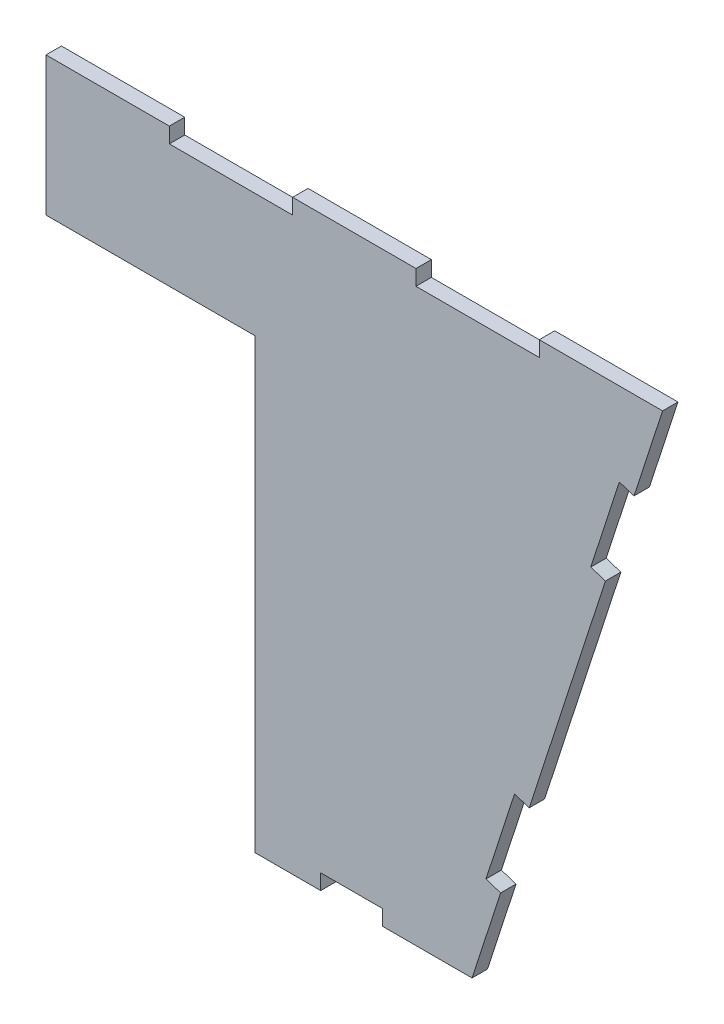
SolidWorks part; units mm, degrees
ref_plane "Front Plane" through (0, 0, 0) normal (0, 0, 1) x (1, 0, 0)
ref_plane "Top Plane" through (0, 0, 0) normal (0, 1, 0) x (1, 0, 0)
ref_plane "Right Plane" through (0, 0, 0) normal (1, 0, 0) x (0, 0, -1)
sketch "Sketch1" plane through (0, 0, 0) normal (0, 0, 1) x (1, 0, 0)
  line L0 (0, 0) -> (5.8868, 18.1176)
  line L1 (39.2452, 120.7842) -> (13.8452, 120.7842)
  line L2 (-87.7548, 120.7842) -> (-87.7548, 92.2092)
  line L4 (33.3584, 102.6666) -> (30.3388, 103.6477)
  line L5 (30.3388, 103.6477) -> (24.452, 85.5301)
  line L6 (24.452, 85.5301) -> (27.4716, 84.5489)
  line L7 (19.6226, 60.3921) -> (-40.3388, 79.8747) construction
  line L8 (33.3584, 102.6666) -> (39.2452, 120.7842)
  line L9 (8.7539, 37.2164) -> (11.7735, 36.2353)
  line L10 (2.8672, 19.0988) -> (8.7539, 37.2164)
  line L11 (5.8868, 18.1176) -> (2.8672, 19.0988)
  line L12 (11.7735, 36.2353) -> (27.4716, 84.5489)
  line L13 (-24.2548, 120.7842) -> (-24.2548, 85.5301) construction
  line L15 (-44.6599, 0) -> (-44.6599, 21.7121) construction
  line L16 (-62.3548, 120.7842) -> (-62.3548, 117.6092)
  line L17 (-62.3548, 117.6092) -> (-36.9548, 117.6092)
  line L18 (-36.9548, 117.6092) -> (-36.9548, 120.7842)
  line L19 (-62.3548, 120.7842) -> (-87.7548, 120.7842)
  line L20 (-87.7548, 138.4514) -> (39.2452, 138.4514) construction
  line L21 (13.8452, 120.7842) -> (13.8452, 117.6092)
  line L22 (13.8452, 117.6092) -> (-11.5548, 117.6092)
  line L23 (-11.5548, 117.6092) -> (-11.5548, 120.7842)
  line L24 (-11.5548, 120.7842) -> (-36.9548, 120.7842)
  line L28 (-44.6599, 0) -> (-31.1774, 0)
  line L29 (-18.4774, 0) -> (-18.4774, 3.175)
  line L30 (-18.4774, 3.175) -> (-31.1774, 3.175)
  line L31 (-31.1774, 3.175) -> (-31.1774, 0)
  line L32 (-18.4774, 0) -> (0, 0)
  line L33 (-44.6599, 0) -> (-44.6599, 92.2092)
  line L34 (-44.6599, 92.2092) -> (-87.7548, 92.2092)
  point P4 (-44.6599, 2.4049)
  point P17 (0, 0)
  point P18 (0, 0)
  point P27 (-24.2548, 138.4514)
  dimension "D2" = 127
  dimension "D3" = 127
  dimension "D4" = 25.4
  dimension "D5" = 19.05
  dimension "D6" = 3.175
  dimension "D7" = 3.175
  dimension "D8" = 25.4
  dimension "D9" = 12.7
  dimension "D13" = 25.4
extrude "Boss-Extrude1" add sketch "Sketch1" along normal blind 3.175
